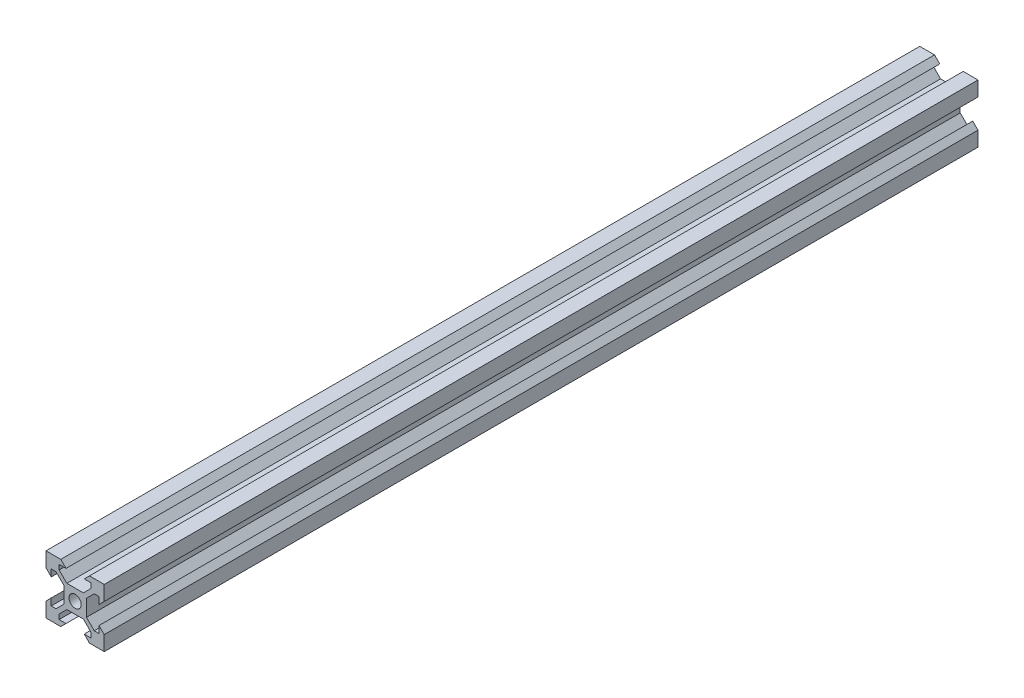
SolidWorks part; units mm, degrees
ref_plane "Front Plane" through (0, 0, 0) normal (0, 0, 1) x (1, 0, 0)
ref_plane "Top Plane" through (0, 0, 0) normal (0, 1, 0) x (1, 0, 0)
ref_plane "Right Plane" through (0, 0, 0) normal (1, 0, 0) x (0, 0, -1)
sketch "Sketch1" plane through (0, 0, 0) normal (0, 0, 1) x (1, 0, 0)
  line L0 (-19.9727, 0) -> (16.5027, 0) construction
  line L1 (-10, -10) -> (10, -10)
  line L2 (-10, -10) -> (-10, 10)
  line L3 (-10, 10) -> (10, 10)
  line L4 (10, -10) -> (10, 10)
  line L5 (-10, -10) -> (10, 10) construction
  line L6 (-10, 10) -> (10, -10) construction
  line L7 (55, 0) -> (-55, 0) construction
  line L8 (0, 14.8997) -> (0, -15.8051) construction
  line L9 (0, -55) -> (0, 55) construction
  line L10 (-4.925, 10) -> (-3.125, 8.2)
  line L11 (-3.125, 8.2) -> (-5.5, 8.2)
  line L12 (-5.5, 8.2) -> (-5.5, 6.5607)
  line L13 (-2.8393, 3.9) -> (2.8393, 3.9)
  line L14 (-5.5, 6.5607) -> (-2.8393, 3.9)
  line L15 (5.5, 6.5607) -> (2.8393, 3.9)
  line L16 (5.5, 8.2) -> (5.5, 6.5607)
  line L17 (3.125, 8.2) -> (5.5, 8.2)
  line L18 (4.925, 10) -> (3.125, 8.2)
  line L19 (10, 4.925) -> (8.2, 3.125)
  line L20 (8.2, 3.125) -> (8.2, 5.5)
  line L21 (8.2, 5.5) -> (6.5607, 5.5)
  line L22 (6.5607, 5.5) -> (3.9, 2.8393)
  line L23 (3.9, -2.8393) -> (3.9, 2.8393)
  line L24 (6.5607, -5.5) -> (3.9, -2.8393)
  line L25 (8.2, -5.5) -> (6.5607, -5.5)
  line L26 (8.2, -3.125) -> (8.2, -5.5)
  line L27 (10, -4.925) -> (8.2, -3.125)
  line L28 (4.925, -10) -> (3.125, -8.2)
  line L29 (-10, 10) -> (-10, -10)
  line L30 (10, -10) -> (-10, -10)
  line L31 (10, 10) -> (10, -10)
  line L32 (10, 10) -> (-10, 10)
  line L33 (3.125, -8.2) -> (5.5, -8.2)
  line L34 (5.5, -8.2) -> (5.5, -6.5607)
  line L35 (5.5, -6.5607) -> (2.8393, -3.9)
  line L36 (2.8393, -3.9) -> (-2.8393, -3.9)
  line L37 (-4.925, -10) -> (-3.125, -8.2)
  line L38 (-3.125, -8.2) -> (-5.5, -8.2)
  line L39 (-5.5, -8.2) -> (-5.5, -6.5607)
  line L40 (-5.5, -6.5607) -> (-2.8393, -3.9)
  line L41 (-10, 4.925) -> (-8.2, 3.125)
  line L42 (-8.2, 3.125) -> (-8.2, 5.5)
  line L43 (-8.2, 5.5) -> (-6.5607, 5.5)
  line L44 (-6.5607, 5.5) -> (-3.9, 2.8393)
  line L45 (-3.9, 2.8393) -> (-3.9, -2.8393)
  line L46 (-6.5607, -5.5) -> (-3.9, -2.8393)
  line L47 (-8.2, -5.5) -> (-6.5607, -5.5)
  line L48 (-8.2, -3.125) -> (-8.2, -5.5)
  line L49 (-10, -4.925) -> (-8.2, -3.125)
  circle A0 centre (0, 0) radius 2.1
  point P0 (0, 0)
  point P21 (0, 3.9)
  dimension "D9" = 4.2
  dimension "D1" = 1.5
  dimension "D2" = 20
  dimension "D3" = 1.8
  dimension "D4" = 3.125
  dimension "D5" = 45
  dimension "D6" = 4.3
  dimension "D7" = 5.5
extrude "Boss-Extrude1" add sketch "Sketch1" along normal mid plane 300 contours L49 L2 L1 L37 L38 L39 L40 L36 L35 L34 L33 L28 L4 L27 L26 L25 L24 L23 L22 L21 L20 L19 L3 L18 L17 L16 L15 L13 L14 L12 L11 L10 L29 L41 L42 L43 L44 L45 L46 L47 L48 A0
